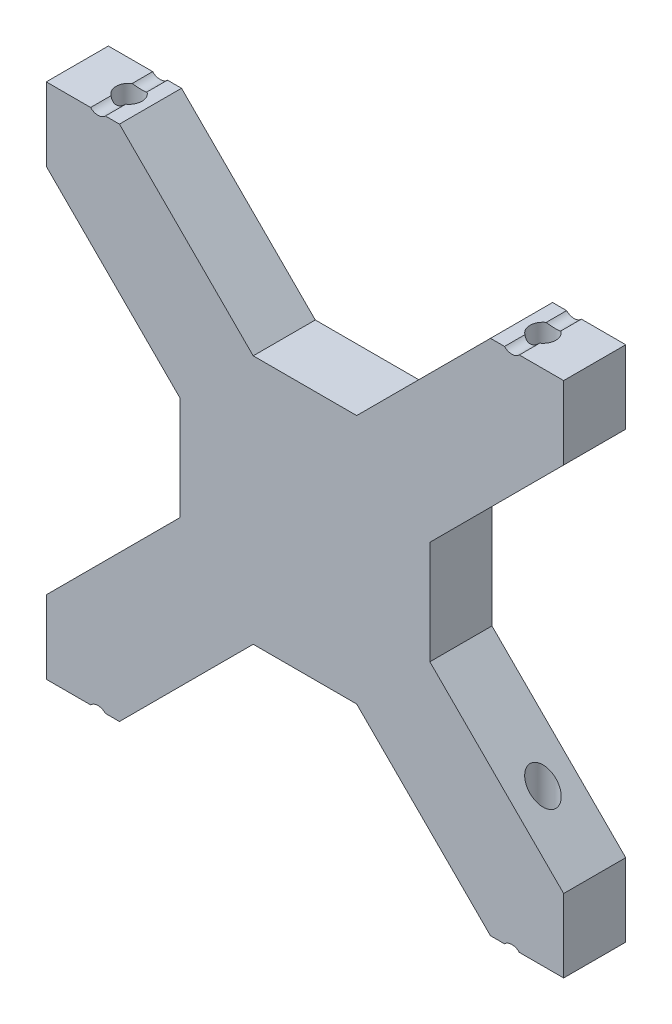
SolidWorks part; units mm, degrees
ref_plane "正面" through (0, 0, 0) normal (0, 0, 1) x (1, 0, 0)
ref_plane "平面" through (0, 0, 0) normal (0, 1, 0) x (1, 0, 0)
ref_plane "右側面" through (0, 0, 0) normal (1, 0, 0) x (0, 0, -1)
sketch "ｽｹｯﾁ1" plane through (0, 0, 0) normal (0, 0, 1) x (1, 0, 0)
  line L0 (-32.0711, 25) -> (-12.0711, 5)
  line L1 (-12.0711, -5) -> (-32.0711, -25)
  line L2 (-32.0711, -25) -> (-17.9289, -25)
  line L3 (-17.9289, -25) -> (-5, -12.0711)
  line L4 (5, -12.0711) -> (17.9289, -25)
  line L5 (17.9289, -25) -> (32.0711, -25)
  line L6 (32.0711, -25) -> (12.0711, -5)
  line L7 (12.0711, 5) -> (32.0711, 25)
  line L8 (32.0711, 25) -> (17.9289, 25)
  line L9 (17.9289, 25) -> (5, 12.0711)
  line L10 (-5, 12.0711) -> (-17.9289, 25)
  line L11 (-17.9289, 25) -> (-32.0711, 25)
  line L12 (-12.0711, 5) -> (-12.0711, -5)
  line L13 (-5, -12.0711) -> (5, -12.0711)
  line L14 (12.0711, -5) -> (12.0711, 5)
  line L15 (5, 12.0711) -> (-5, 12.0711)
  line L16 (12.0711, 5) -> (-12.0711, -5) construction
  line L17 (-12.0711, 5) -> (12.0711, -5) construction
  line L18 (-12.0711, 5) -> (12.0711, 5) construction
  line L19 (5, 12.0711) -> (-5, -12.0711) construction
  line L20 (-5, 12.0711) -> (5, -12.0711) construction
  point P1 (0, 0)
  point P11 (0, 0)
  dimension "D1" = 10
  dimension "D2" = 135
  dimension "D3" = 10
  dimension "D4" = 10
  dimension "D5" = 50
  dimension "D6" = 135
extrude "ﾎﾞｽ - 押し出し1" add sketch "ｽｹｯﾁ1" along normal blind 6
sketch "ｽｹｯﾁ2" plane through (0, 0, 6) normal (0, 0, 1) x (1, 0, 0)
  line L0 (0, 0) -> (0, 38.1314) construction
  line L1 (-17.9289, 25) -> (-32.0711, 25) construction
  line L2 (-20.7141, 25) -> (-19.2859, 25)
  line L3 (20.7141, 25) -> (19.2859, 25)
  arc A0 (-20.7141, 25) -> (-19.2859, 25) centre (-20, 25.7) ccw
  arc A1 (20.7141, 25) -> (19.2859, 25) centre (20, 25.7) cw
  dimension "D1" = 20
  dimension "D2" = 2
  dimension "D3" = 0.7
extrude "ｶｯﾄ - 押し出し1" cut sketch "ｽｹｯﾁ2" against normal through all
fillet "ﾌｨﾚｯﾄ1" radius 2 2 edges at (32.0711, 25, 3) (-32.0711, 25, 3)
ref_plane "平面1" through (0, 0, 0) normal (0, 1, 0) x (1, 0, 0)
mirror "ﾐﾗｰ3" about plane through (0, 0, 0) normal (0, 1, 0) of "ｶｯﾄ - 押し出し1", "ﾌｨﾚｯﾄ1"
sketch "ｽｹｯﾁ3" plane through (0, 25, 0) normal (0, 1, 0) x (1, 0, 0)
  line L0 (-29.2426, -3) -> (29.2426, -3) construction
  line L1 (-29.2426, 0) -> (-29.2426, -6) construction
  line L2 (29.2426, -6) -> (29.2426, 0) construction
  line L3 (-20, 0) -> (-20, -6) construction
  line L4 (-19.2859, 0) -> (-20.7141, 0) construction
  line L5 (-20.7141, -6) -> (-19.2859, -6) construction
  line L6 (20, 0) -> (20, -6) construction
  line L7 (20.7141, 0) -> (19.2859, 0) construction
  line L8 (19.2859, -6) -> (20.7141, -6) construction
  circle A0 centre (-20, -3) radius 1.25
  circle A1 centre (20, -3) radius 1.25
  point P10 (22.5, -3)
  point P23 (-22.5, -3)
  dimension "D1" = 2.5
extrude "ｶｯﾄ - 押し出し2" cut sketch "ｽｹｯﾁ3" against normal through all
sketch "ｽｹｯﾁ4" plane through (0, 0, 6) normal (0, 0, 1) x (1, 0, 0)
  line L0 (27.2426, 25) -> (20.7141, 25) construction
  line L2 (-25, -25) -> (-25, 25)
  line L4 (25, -25) -> (25, 25)
  line L5 (-25, -25) -> (25, 25) construction
  line L6 (-25, 25) -> (25, -25) construction
  line L7 (-27.2426, -25) -> (-20.7141, -25) construction
  line L8 (29.2426, 25) -> (25, 25)
  line L9 (29.2426, 25) -> (29.2426, -25)
  line L10 (29.2426, -25) -> (25, -25)
  line L11 (-29.2426, 25) -> (-29.2426, -25)
  line L12 (29.2426, 25) -> (-29.2426, -25) construction
  line L13 (29.2426, -25) -> (-29.2426, 25) construction
  line L14 (-25, -25) -> (-29.2426, -25)
  line L15 (-25, 25) -> (-29.2426, 25)
  arc A0 (-28.6569, -21.5858) -> (-27.2426, -25) centre (-27.2426, -23) ccw construction
  point P0 (0, 0)
  point P8 (0, 0)
extrude "ｶｯﾄ - 押し出し3" cut sketch "ｽｹｯﾁ4" against normal through all
